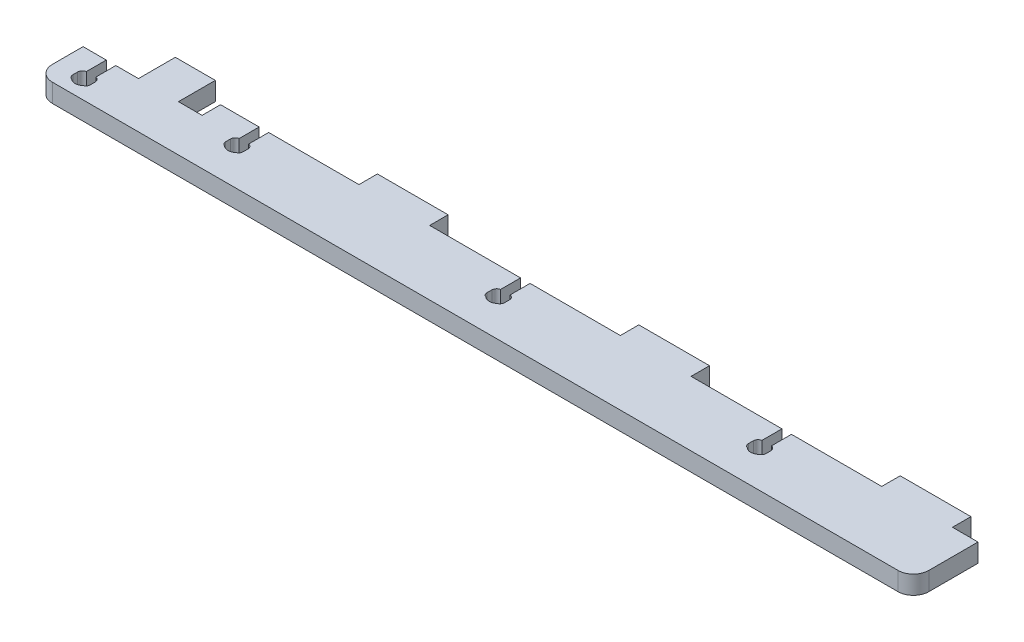
SolidWorks part; units mm, degrees
ref_plane "Alzado" through (0, 0, 0) normal (0, 0, 1) x (1, 0, 0)
ref_plane "Planta" through (0, 0, 0) normal (0, 1, 0) x (1, 0, 0)
ref_plane "Vista lateral" through (0, 0, 0) normal (1, 0, 0) x (0, 0, -1)
sketch "Croquis1" plane through (0, 0, 0) normal (0, 1, 0) x (1, 0, 0)
  line L0 (-113.4766, -5.7424) -> (-113.4766, -11.2465) construction
  line L1 (-122.4766, -5.7424) -> (-114.9266, -5.7424)
  line L2 (-122.4766, -5.7424) -> (-122.4766, -15.7424)
  line L3 (-117.4766, -20.7424) -> (157.5234, -20.7424)
  line L4 (162.5234, -0.7424) -> (162.5234, -15.7424)
  line L5 (-114.9266, -12.2426) -> (-114.9266, -5.7424)
  line L6 (-111.8266, -12.2426) -> (-111.8266, -5.7424)
  line L7 (-110.5363, -13.7707) -> (-110.5363, -15.3207)
  line L8 (-111.2451, -16.6226) -> (-111.4144, -16.6226)
  line L9 (-115.5081, -16.6226) -> (-115.3389, -16.6226)
  line L10 (-116.217, -13.7707) -> (-116.217, -15.3207)
  line L11 (-69.7766, 0.2576) -> (-69.7766, -5.2465) construction
  line L12 (-105.4766, -5.7424) -> (-104.4766, -5.7424)
  line L13 (131.2234, 0.2576) -> (101.8734, 0.2576)
  line L14 (-104.4766, 6.2576) -> (-91.4766, 6.2576)
  line L15 (46.2234, 0.2576) -> (16.8734, 0.2576)
  line L16 (-69.7766, 0.2576) -> (-69.7766, -5.2465) construction
  line L17 (162.5234, -0.7424) -> (162.5234, 0.2576)
  line L18 (162.5234, 0.2576) -> (154.2234, 0.2576)
  line L19 (-83.7766, -5.7424) -> (-83.7766, 0.2576)
  line L20 (-71.2266, -6.2426) -> (-71.2266, 0.2576)
  line L21 (-68.1266, -6.2426) -> (-68.1266, 0.2576)
  line L22 (-66.8363, -7.7707) -> (-66.8363, -9.3207)
  line L23 (-67.5451, -10.6226) -> (-67.7144, -10.6226)
  line L24 (-71.8081, -10.6226) -> (-71.6389, -10.6226)
  line L25 (-72.517, -7.7707) -> (-72.517, -9.3207)
  line L26 (46.2234, 6.2576) -> (69.2234, 6.2576)
  line L27 (-39.7766, 0.2576) -> (-38.7766, 0.2576)
  line L28 (-15.7766, 0.2576) -> (-14.7766, 0.2576)
  line L29 (-38.7766, 6.2576) -> (-15.7766, 6.2576)
  line L30 (-38.7766, 0.2576) -> (-68.1266, 0.2576)
  line L31 (-91.4766, -5.7424) -> (-90.4766, -5.7424)
  line L32 (-91.4766, -5.7424) -> (-83.7766, -5.7424)
  line L33 (13.7734, -6.2426) -> (13.7734, 0.2576)
  line L34 (16.8734, -6.2426) -> (16.8734, 0.2576)
  line L35 (18.1637, -7.7707) -> (18.1637, -9.3207)
  line L36 (17.4549, -10.6226) -> (17.2856, -10.6226)
  line L37 (13.1919, -10.6226) -> (13.3611, -10.6226)
  line L38 (12.483, -7.7707) -> (12.483, -9.3207)
  line L39 (15.2234, 0.2576) -> (15.2234, -5.2465) construction
  line L40 (15.2234, 0.2576) -> (15.2234, -5.2465) construction
  line L41 (131.2234, 6.2576) -> (154.2234, 6.2576)
  line L44 (98.7734, -6.2426) -> (98.7734, 0.2576)
  line L45 (101.8734, -6.2426) -> (101.8734, 0.2576)
  line L46 (103.1637, -7.7707) -> (103.1637, -9.3207)
  line L47 (102.4549, -10.6226) -> (102.2856, -10.6226)
  line L48 (98.1919, -10.6226) -> (98.3611, -10.6226)
  line L49 (97.483, -7.7707) -> (97.483, -9.3207)
  line L50 (100.2234, 0.2576) -> (100.2234, -5.2465) construction
  line L51 (100.2234, 0.2576) -> (100.2234, -5.2465) construction
  line L52 (-71.2266, 0.2576) -> (-83.7766, 0.2576)
  line L53 (-111.8266, -5.7424) -> (-104.4766, -5.7424)
  line L54 (13.7734, 0.2576) -> (-15.7766, 0.2576)
  line L55 (98.7734, 0.2576) -> (69.2234, 0.2576)
  line L56 (-91.4766, 6.2576) -> (-91.4766, -5.7424)
  line L57 (-104.4766, 6.2576) -> (-104.4766, -5.7424)
  line L58 (-38.7766, 6.2576) -> (-38.7766, 0.2576)
  line L59 (-15.7766, 6.2576) -> (-15.7766, 0.2576)
  line L60 (46.2234, 6.2576) -> (46.2234, 0.2576)
  line L61 (69.2234, 6.2576) -> (69.2234, 0.2576)
  line L62 (131.2234, 6.2576) -> (131.2234, 0.2576)
  line L63 (154.2234, 6.2576) -> (154.2234, 0.2576)
  arc A0 (-110.5363, -13.7707) -> (-111.8266, -12.2426) centre (-112.0863, -13.7707) ccw
  arc A1 (-111.2451, -16.6226) -> (-110.5363, -15.3207) centre (-112.0863, -15.3207) ccw
  arc A2 (-115.3389, -16.6226) -> (-111.4144, -16.6226) centre (-113.3766, -14.6611) ccw
  arc A3 (-115.5081, -16.6226) -> (-116.217, -15.3207) centre (-114.667, -15.3207) cw
  arc A4 (-116.217, -13.7707) -> (-114.9266, -12.2426) centre (-114.667, -13.7707) cw
  arc A5 (-66.8363, -7.7707) -> (-68.1266, -6.2426) centre (-68.3863, -7.7707) ccw
  arc A6 (-67.5451, -10.6226) -> (-66.8363, -9.3207) centre (-68.3863, -9.3207) ccw
  arc A7 (-71.6389, -10.6226) -> (-67.7144, -10.6226) centre (-69.6766, -8.6611) ccw
  arc A8 (-71.8081, -10.6226) -> (-72.517, -9.3207) centre (-70.967, -9.3207) cw
  arc A9 (-72.517, -7.7707) -> (-71.2266, -6.2426) centre (-70.967, -7.7707) cw
  arc A10 (18.1637, -7.7707) -> (16.8734, -6.2426) centre (16.6137, -7.7707) ccw
  arc A11 (17.4549, -10.6226) -> (18.1637, -9.3207) centre (16.6137, -9.3207) ccw
  arc A12 (13.3611, -10.6226) -> (17.2856, -10.6226) centre (15.3234, -8.6611) ccw
  arc A13 (13.1919, -10.6226) -> (12.483, -9.3207) centre (14.033, -9.3207) cw
  arc A14 (12.483, -7.7707) -> (13.7734, -6.2426) centre (14.033, -7.7707) cw
  arc A15 (103.1637, -7.7707) -> (101.8734, -6.2426) centre (101.6137, -7.7707) ccw
  arc A16 (102.4549, -10.6226) -> (103.1637, -9.3207) centre (101.6137, -9.3207) ccw
  arc A17 (98.3611, -10.6226) -> (102.2856, -10.6226) centre (100.3234, -8.6611) ccw
  arc A18 (98.1919, -10.6226) -> (97.483, -9.3207) centre (99.033, -9.3207) cw
  arc A19 (97.483, -7.7707) -> (98.7734, -6.2426) centre (99.033, -7.7707) cw
  arc A20 (162.5234, -15.7424) -> (157.5234, -20.7424) centre (157.5234, -15.7424) cw
  arc A21 (-122.4766, -15.7424) -> (-117.4766, -20.7424) centre (-117.4766, -15.7424) ccw
  point P6 (-113.4766, -5.7424)
  point P35 (-69.7766, 0.2576)
  point P109 (162.5234, -20.7424)
  point P112 (-122.4766, -20.7424)
  dimension "D15" = 5
  dimension "D1" = 285
  dimension "D3" = 9
  dimension "D7" = 6
  dimension "D13" = 3
  dimension "D16" = 15
  dimension "D20" = 3
extrude "Saliente-Extruir1" add sketch "Croquis1" along normal blind 6 contours L2 A21 L3 A20 L4 L17 L18 L63 L41 L62 L13 L45 A15 L46 A16 L47 A17 L48 A18 L49 A19 L44 L55 L61 L26 L60 L15 L34 A10 L35 A11 L36 A12 L37 A13 L38 A14 L33 L54 L28 L59 L29 L58 L27 L30 L21 A5 L22 A6 L23 A7
